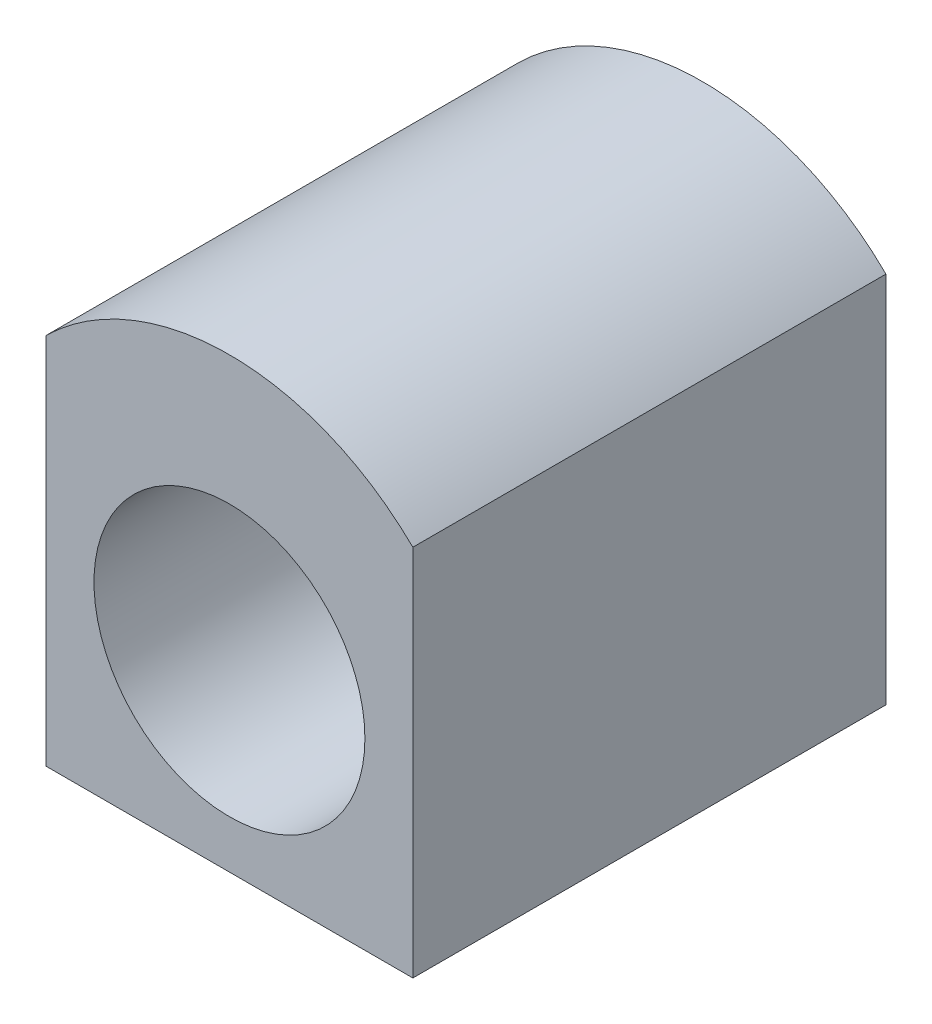
SolidWorks part; units mm, degrees
ref_plane "Спереди" through (0, 0, 0) normal (0, 0, 1) x (1, 0, 0)
ref_plane "Сверху" through (0, 0, 0) normal (0, 1, 0) x (1, 0, 0)
ref_plane "Справа" through (0, 0, 0) normal (1, 0, 0) x (0, 0, -1)
sketch "Эскиз1" plane through (0, 0, 0) normal (0, 0, 1) x (1, 0, 0)
  line L0 (-8.8, 0) -> (8.8, 0)
  line L1 (8.8, 0) -> (8.8, 17.9)
  line L2 (-8.8, 0) -> (-8.8, 17.9)
  arc A0 (-8.8, 17.9) -> (8.8, 17.9) centre (0, 8.9444) cw
  point P3 (0, 21.5)
  point P8 (0, 21.5)
  dimension "D1" = 17.6
  dimension "D2" = 8.8
  dimension "D3" = 21.5
  dimension "D4" = 17.9
extrude "Бобышка-Вытянуть1" add sketch "Эскиз1" along normal blind 22.7
sketch "Эскиз2" plane through (0, 0, 22.7) normal (0, 0, 1) x (1, 0, 0)
  circle A0 centre (0, 8.8) radius 6.5
  dimension "D1" = 13
  dimension "D2" = 8.8
extrude "Вырез-Вытянуть1" cut sketch "Эскиз2" against normal through all
ref_plane "Плоскость1" through (0, 0, 0) normal (1, 0, 0) x (0, 0, -1)
